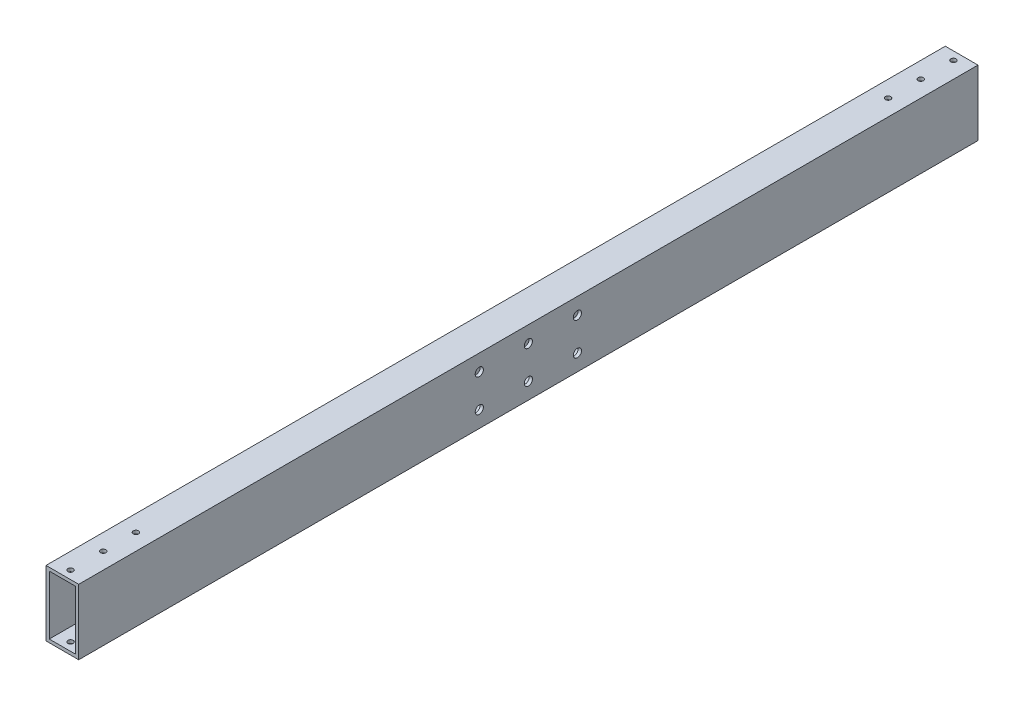
SolidWorks part; units mm, degrees
material "6061-T6 (SS)"
ref_plane "Front Plane" through (0, 0, 0) normal (0, 0, 1) x (1, 0, 0)
ref_plane "Top Plane" through (0, 0, 0) normal (0, 1, 0) x (1, 0, 0)
ref_plane "Right Plane" through (0, 0, 0) normal (1, 0, 0) x (0, 0, -1)
sketch "Sketch1" plane through (0, 0, 0) normal (0, 0, 1) x (1, 0, 0)
  line L1 (-12.7, -25.4) -> (12.7, -25.4)
  line L2 (-12.7, -25.4) -> (-12.7, 25.4)
  line L3 (-12.7, 25.4) -> (12.7, 25.4)
  line L4 (12.7, -25.4) -> (12.7, 25.4)
  line L5 (-12.7, -25.4) -> (12.7, 25.4) construction
  line L6 (-12.7, 25.4) -> (12.7, -25.4) construction
  point P0 (0, 0)
  dimension "D1" = 50.8
  dimension "D2" = 25.4
extrude "Extrude-Thin1" add sketch "Sketch1" along normal blind 698.5 thin thin type one direction reverse wall 2.54
sketch "Sketch2" plane through (0, 25.4, 0) normal (0, 1, 0) x (1, 0, 0)
  line L0 (12.7, 0) -> (-12.7, 0) construction
  line L1 (-12.7, -349.25) -> (12.7, -349.25) construction
  line L2 (-12.7, -698.5) -> (-12.7, 0) construction
  line L3 (12.7, -698.5) -> (12.7, 0) construction
  circle A0 centre (0, -6.35) radius 2.0701
  circle A1 centre (0, -31.75) radius 2.0701
  circle A2 centre (0, -57.15) radius 2.0701
  circle A3 centre (0, -641.35) radius 2.0701
  circle A4 centre (0, -666.75) radius 2.0701
  circle A5 centre (0, -692.15) radius 2.0701
  point P8 (0, 0)
  dimension "D1" = 6.35
  dimension "D2" = 4.1402
  dimension "D4" = 25.4
  dimension "D3" = 3
extrude "Cut-Extrude1" cut sketch "Sketch2" against normal through all
sketch "Sketch3" plane through (-12.7, 0, 0) normal (-1, 0, 0) x (0, 0, 1)
  line L0 (0, 0) -> (311.15, 0) construction
  line L1 (311.15, 0) -> (311.15, 12.7) construction
  line L2 (311.15, 12.7) -> (387.35, 12.7) construction
  line L3 (387.35, 12.7) -> (387.35, -12.7) construction
  line L4 (387.35, -12.7) -> (311.15, -12.7) construction
  line L5 (311.15, -12.7) -> (311.15, 0) construction
  line L6 (387.35, 0) -> (698.5, 0) construction
  line L7 (698.5, 25.4) -> (698.5, -25.4) construction
  circle A0 centre (311.15, 12.7) radius 3.175
  circle A1 centre (311.15, -12.7) radius 3.175
  circle A2 centre (387.35, -12.7) radius 3.175
  circle A3 centre (387.35, 12.7) radius 3.175
  circle A4 centre (349.25, 12.7) radius 3.175
  circle A5 centre (349.25, -12.7) radius 3.175
  dimension "D4" = 6.35
  dimension "D1" = 311.15
  dimension "D2" = 76.2
  dimension "D3" = 25.4
extrude "Cut-Extrude2" cut sketch "Sketch3" against normal through all
